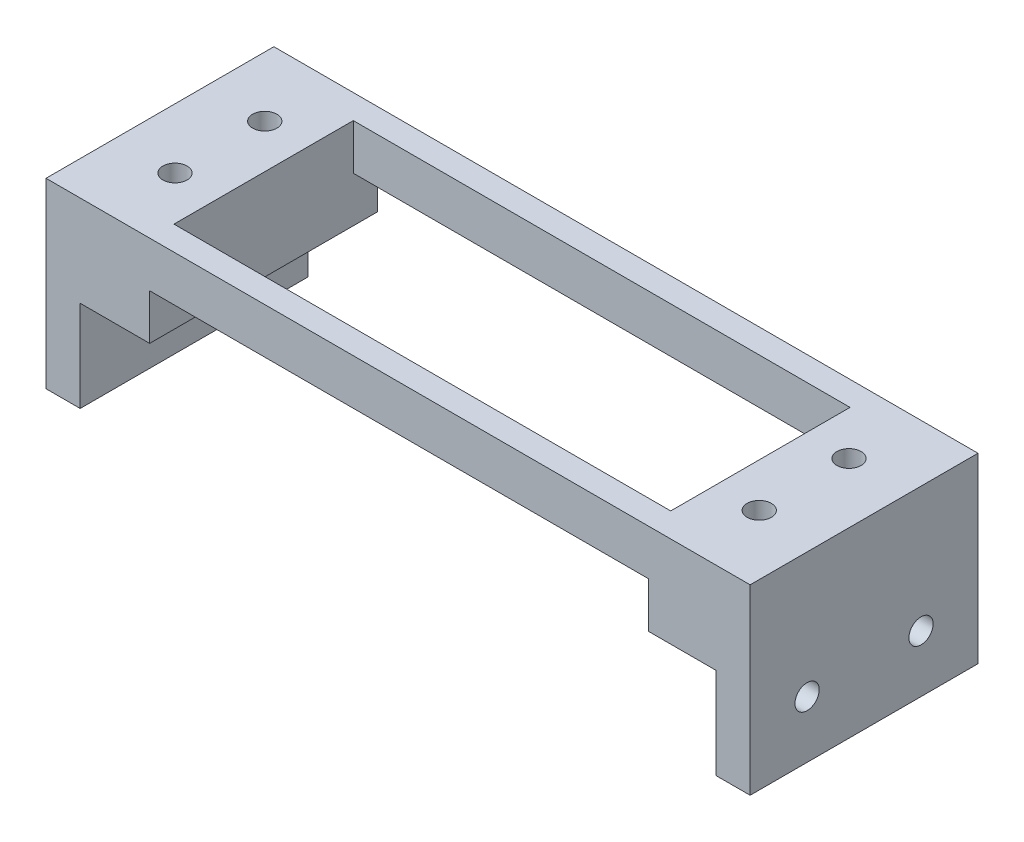
SolidWorks part; units mm, degrees
ref_plane "Front Plane" through (0, 0, 0) normal (0, 0, 1) x (1, 0, 0)
ref_plane "Top Plane" through (0, 0, 0) normal (0, 1, 0) x (1, 0, 0)
ref_plane "Right Plane" through (0, 0, 0) normal (1, 0, 0) x (0, 0, -1)
sketch "Sketch1" plane through (0, 0, 0) normal (0, 1, 0) x (1, 0, 0)
  line L1 (35.433, -12.7) -> (-35.433, -12.7)
  line L2 (35.433, -12.7) -> (35.433, 12.7)
  line L3 (35.433, 12.7) -> (-35.433, 12.7)
  line L4 (-35.433, -12.7) -> (-35.433, 12.7)
  line L5 (35.433, -12.7) -> (-35.433, 12.7) construction
  line L6 (35.433, 12.7) -> (-35.433, -12.7) construction
  line L7 (27.686, -9.9949) -> (-27.686, -9.9949)
  line L8 (27.686, -9.9949) -> (27.686, 9.9949)
  line L9 (27.686, 9.9949) -> (-27.686, 9.9949)
  line L10 (-27.686, -9.9949) -> (-27.686, 9.9949)
  line L11 (27.686, -9.9949) -> (-27.686, 9.9949) construction
  line L12 (27.686, 9.9949) -> (-27.686, -9.9949) construction
  point P0 (0, 0)
  point P6 (0, 0)
  dimension "D1" = 70.866
  dimension "D2" = 25.4
  dimension "D3" = 19.9898
  dimension "D4" = 55.372
extrude "Boss-Extrude1" add sketch "Sketch1" along normal blind 5.08
sketch "Sketch7" plane through (0, 0, 0) normal (0, -1, 0) x (1, 0, 0)
  line L0 (-35.433, 12.7) -> (35.433, 12.7) construction
  line L1 (-35.433, 12.7) -> (-27.686, 12.7)
  line L2 (-35.433, 12.7) -> (-35.433, -12.7)
  line L3 (-35.433, -12.7) -> (-27.686, -12.7)
  line L4 (-27.686, 12.7) -> (-27.686, -12.7)
  line L5 (-35.433, -12.7) -> (-35.433, 12.7) construction
  line L6 (35.433, -12.7) -> (-35.433, -12.7) construction
  line L8 (35.433, 12.7) -> (27.9092, 12.7)
  line L9 (35.433, 12.7) -> (35.433, -12.7)
  line L10 (35.433, -12.7) -> (27.9092, -12.7)
  line L11 (27.9092, 12.7) -> (27.9092, -12.7)
extrude "Boss-Extrude2" add sketch "Sketch7" along normal blind 5.08
sketch "Sketch8" plane through (0, 0, 12.7) normal (0, 0, 1) x (1, 0, 0)
  line L0 (35.433, 5.08) -> (35.433, -15.24)
  line L1 (35.433, 5.08) -> (39.243, 5.08)
  line L2 (39.243, 5.08) -> (39.243, -5.08)
  line L3 (39.243, -5.08) -> (39.243, -15.24)
  line L4 (39.243, -15.24) -> (35.433, -15.24)
  dimension "D1" = 10.16
  dimension "D2" = 3.81
  dimension "D3" = 10.16
extrude "Boss-Extrude3" add sketch "Sketch8" against normal blind 25.4
mirror "Mirror1" about plane through (0, 0, 0) normal (1, 0, 0) of "Boss-Extrude3"
hole_wizard "Tap Drill for #6-32 Tap1" positions "Sketch4" profile "Sketch5" hole size "#6-32" standard "ANSI Inch"
sketch "Sketch4" plane through (0, 5.08, 0) normal (0, 1, 0) x (1, 0, 0)
  line L2 (32.5628, -5.0038) -> (-32.5628, -5.0038)
  line L3 (32.5628, -5.0038) -> (32.5628, 5.0038)
  line L4 (32.5628, 5.0038) -> (-32.5628, 5.0038)
  line L5 (-32.5628, -5.0038) -> (-32.5628, 5.0038)
  line L6 (32.5628, -5.0038) -> (-32.5628, 5.0038) construction
  line L7 (32.5628, 5.0038) -> (-32.5628, -5.0038) construction
  point P0 (-32.5628, 5.0038)
  point P2 (-32.5628, -5.0038)
  point P4 (32.5628, 5.0038)
  point P6 (32.5628, -5.0038)
  point P109 (0, 0)
  dimension "D1" = 65.1256
  dimension "D2" = 10.0076
sketch "Sketch5" plane through (-32.5628, 5.08, -5.0038) normal (1, 0, 0) x (0, 0, 1)
  line L0 (0, 0) -> (0, 10.9727)
  line L1 (0, 10.9727) -> (1.3525, 10.16)
  line L2 (1.3525, 10.16) -> (1.3525, 0)
  line L5 (1.3525, 0) -> (0, 0)
  line L10 (0, 10.9727) -> (-1.3526, 10.16) construction
  line L11 (0, -6.35) -> (0, 107.95) construction
  dimension "Hole Dia." = 2.7051
  dimension "Hole Depth" = 10.16
  dimension "Drill Angle" = 118
hole_wizard "Tap Drill for #6-32 Tap2" positions "Sketch9" profile "Sketch10" hole size "#6-32" standard "ANSI Inch"
sketch "Sketch9" plane through (-39.243, 0, 0) normal (-1, 0, 0) x (0, 0, 1)
  line L0 (-6.35, -8.89) -> (6.35, -8.89)
  line L1 (-12.7, -15.24) -> (12.7, -15.24) construction
  point P0 (-6.35, -8.89)
  point P2 (6.35, -8.89)
  point P8 (0, -8.89)
  point P11 (0, -15.24)
  dimension "D1" = 12.7
  dimension "D2" = 0
  dimension "D3" = 6.35
sketch "Sketch10" plane through (-39.243, -8.89, -6.35) normal (0, 1, 0) x (0, 0, 1)
  line L0 (0, 0) -> (0, 10.9727)
  line L1 (0, 10.9727) -> (1.3525, 10.16)
  line L2 (1.3525, 10.16) -> (1.3525, 0)
  line L5 (1.3525, 0) -> (0, 0)
  line L10 (0, 10.9727) -> (-1.3525, 10.16) construction
  line L11 (0, -6.35) -> (0, 107.95) construction
  dimension "Hole Dia." = 2.7051
  dimension "Hole Depth" = 10.16
  dimension "Drill Angle" = 118
mirror "Mirror2" about plane through (0, 0, 0) normal (1, 0, 0) of "Tap Drill for #6-32 Tap2"
